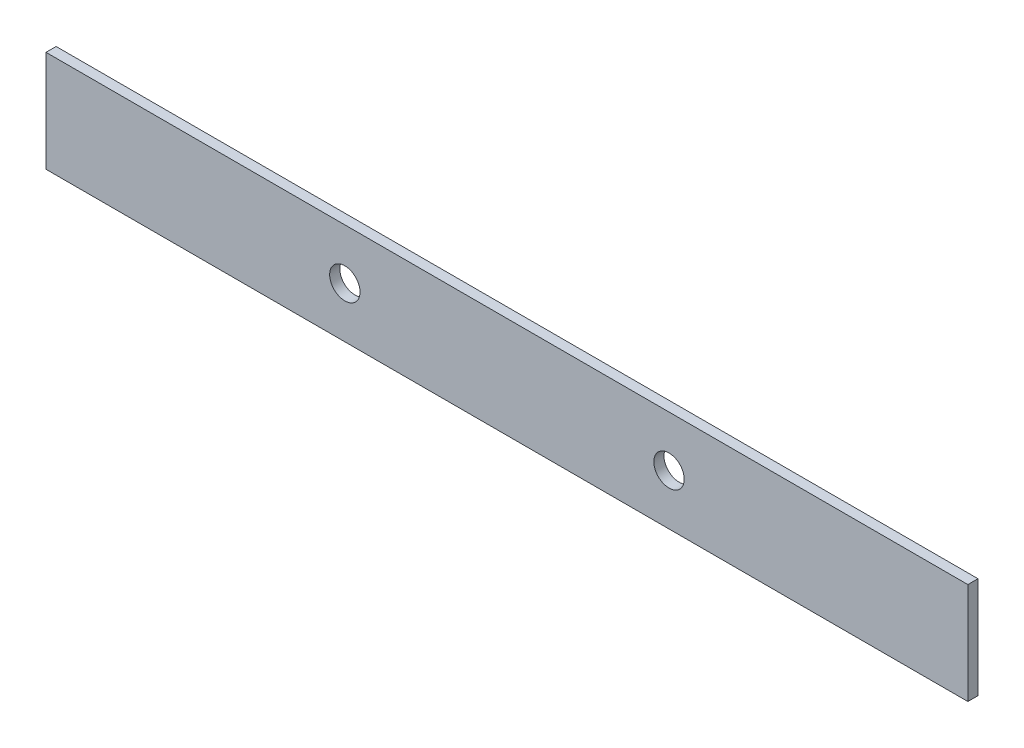
SolidWorks part; units mm, degrees
ref_plane "Plan de face" through (0, 0, 0) normal (0, 0, 1) x (1, 0, 0)
ref_plane "Plan de dessus" through (0, 0, 0) normal (0, 1, 0) x (1, 0, 0)
ref_plane "Plan de droite" through (0, 0, 0) normal (1, 0, 0) x (0, 0, -1)
sketch "Esquisse1" plane through (0, 0, 0) normal (0, 0, 1) x (1, 0, 0)
  line L0 (455, 100) -> (455, 0) construction
  line L1 (0, 0) -> (910, 0)
  line L2 (0, 0) -> (0, 100)
  line L3 (0, 100) -> (910, 100)
  line L4 (910, 0) -> (910, 100)
  line L5 (0, 50) -> (910, 50) construction
  circle A0 centre (295, 50) radius 15
  circle A1 centre (615, 50) radius 15
  dimension "D3" = 30
  dimension "D1" = 910
  dimension "D2" = 100
  dimension "D4" = 160
extrude "Boss.-Extru.1" add sketch "Esquisse1" along normal blind 10
